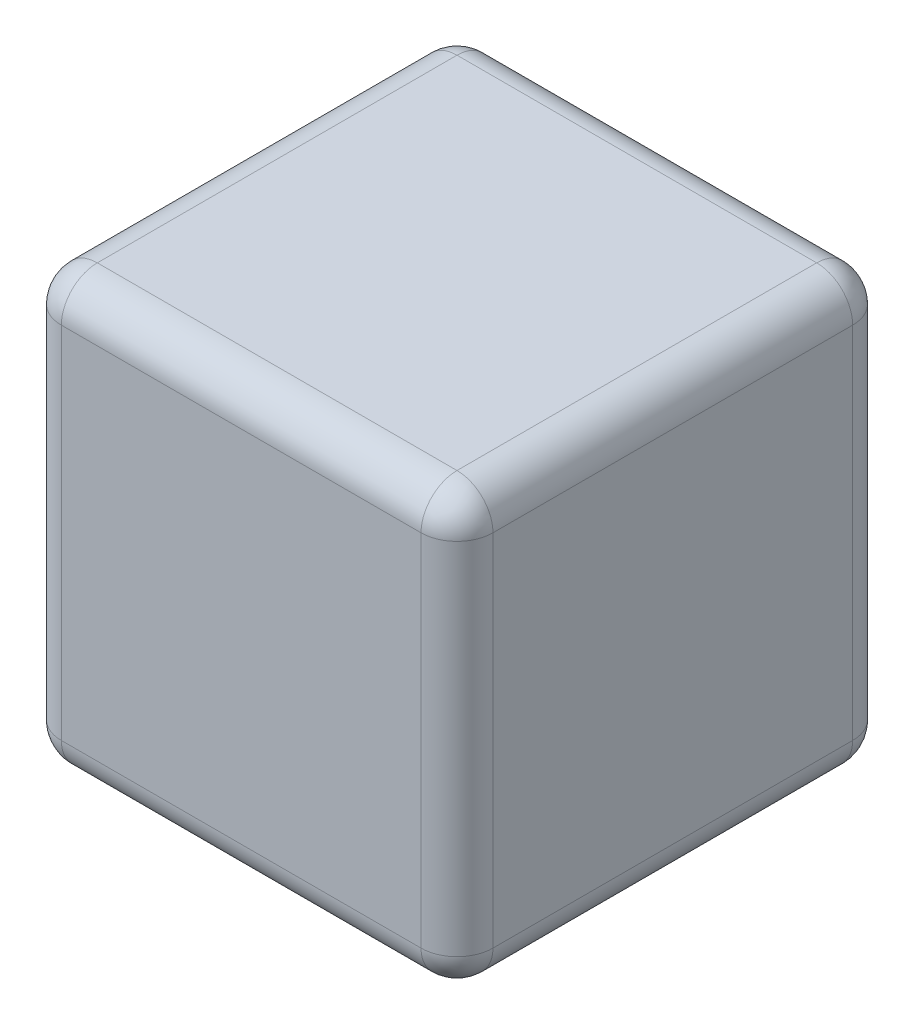
SolidWorks part; units mm, degrees
ref_plane "Front Plane" through (0, 0, 0) normal (0, 0, 1) x (1, 0, 0)
ref_plane "Top Plane" through (0, 0, 0) normal (0, 1, 0) x (1, 0, 0)
ref_plane "Right Plane" through (0, 0, 0) normal (1, 0, 0) x (0, 0, -1)
sketch "Sketch1" plane through (0, 0, 0) normal (0, 0, 1) x (1, 0, 0)
  line L1 (-1.5, 1.5) -> (1.5, 1.5)
  line L2 (-1.5, 1.5) -> (-1.5, -1.5)
  line L3 (-1.5, -1.5) -> (1.5, -1.5)
  line L4 (1.5, 1.5) -> (1.5, -1.5)
  line L5 (-1.5, 1.5) -> (1.5, -1.5) construction
  line L6 (-1.5, -1.5) -> (1.5, 1.5) construction
  point P0 (0, 0)
  dimension "D1" = 3
  dimension "D2" = 3
extrude "Boss-Extrude1" add sketch "Sketch1" along normal blind 3
fillet "Fillet1" radius 0.25 12 edges at (1.5, -1.5, 1.5) (0, -1.5, 0) (1.5, 0, 0) (-1.5, 0, 0) (-1.5, -1.5, 1.5) (0, -1.5, 3) (1.5, 0, 3) (1.5, 1.5, 1.5) (0, 1.5, 0) (-1.5, 1.5, 1.5) (-1.5, 0, 3) (0, 1.5, 3)
